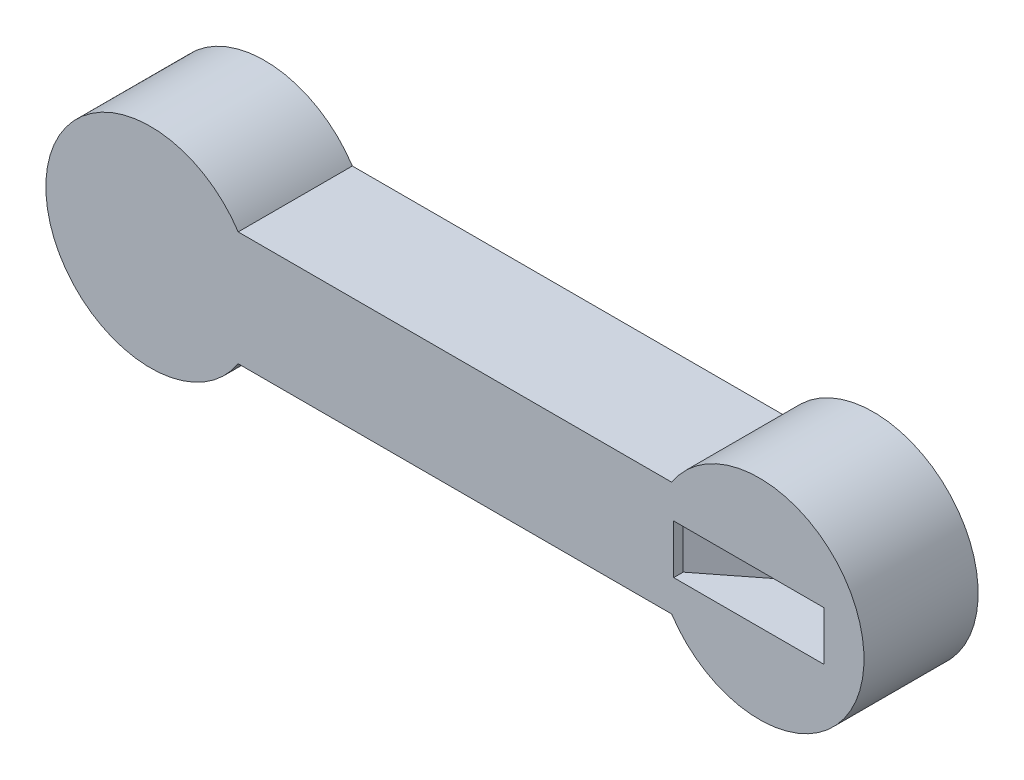
SolidWorks part; units mm, degrees
ref_plane "Front Plane" through (0, 0, 0) normal (0, 0, 1) x (1, 0, 0)
ref_plane "Top Plane" through (0, 0, 0) normal (0, 1, 0) x (1, 0, 0)
ref_plane "Right Plane" through (0, 0, 0) normal (1, 0, 0) x (0, 0, -1)
sketch "Sketch1" plane through (0, 0, 0) normal (0, 0, 1) x (1, 0, 0)
  line L1 (0, 15) -> (160, 15)
  line L2 (0, 15) -> (0, -15)
  line L3 (0, -15) -> (160, -15)
  line L4 (160, 15) -> (160, -15)
  circle A0 centre (0, 0) radius 27.5
  circle A1 centre (160, 0) radius 27.5
  circle A2 centre (0, 0) radius 20
  point P9 (0, 0)
  dimension "D1" = 55
  dimension "D4" = 55
  dimension "D5" = 40
  dimension "D2" = 160
  dimension "D3" = 30
extrude "Boss-Extrude1" add sketch "Sketch1" along normal blind 30 contours L3 A1 L1 L4 | A1 L1 A0 L3 | L1 A1 L3 L4 | A2 L3 A0 L1 | A2 L1 A0 L3 | L3 A2 L1 L2 | L1 A2 L3 L2
sketch "Sketch16" plane through (0, 0, 0) normal (0, 0, -1) x (-1, 0, 0)
  line L0 (-136.9511, -15) -> (-148.5193, -6.45) construction
  line L1 (-148.5193, -6.45) -> (-181.9193, -6.45)
  line L2 (-148.5193, -6.45) -> (-148.5193, 6.45)
  line L3 (-148.5193, 6.45) -> (-181.9193, 6.45)
  line L4 (-181.9193, -6.45) -> (-181.9193, 6.45)
  line L5 (-23.0489, -15) -> (-136.9511, -15) construction
  line L7 (-148.5193, 6.45) -> (-136.9511, 15) construction
  arc A1 (-136.9511, 15) -> (-136.9511, -15) centre (-160, 0) ccw construction
  point P5 (0, 0)
  point P8 (0, 0)
  dimension "D1" = 11.5682
  dimension "D2" = 33.4
  dimension "D3" = 12.9
extrude "Cut-Extrude10" cut sketch "Sketch16" against normal blind 4.5
sketch "Sketch17" plane through (0, 0, 0) normal (0, 0, -1) x (-1, 0, 0)
  line L1 (-176.95, 6.45) -> (-153.4979, 6.45)
  line L2 (-176.95, 6.45) -> (-176.95, -6.45)
  line L3 (-176.95, -6.45) -> (-153.4979, -6.45)
  line L4 (-148.5193, -6.45) -> (-148.5193, 6.45)
  line L5 (-148.5193, 6.45) -> (-181.9193, 6.45)
  line L6 (-181.9193, 6.45) -> (-181.9193, -6.45)
  line L7 (-181.9193, -6.45) -> (-148.5193, -6.45)
  line L8 (-148.5193, -6.45) -> (-148.5193, 6.45)
  line L9 (-148.5193, 6.45) -> (-181.9193, 6.45)
  line L10 (-181.9193, 6.45) -> (-181.9193, -6.45)
  line L11 (-181.9193, -6.45) -> (-148.5193, -6.45)
  line L12 (-153.4979, 6.45) -> (-153.4979, -6.45)
  line M9 (-181.9193, 6.45) -> (-148.5193, 6.45)
  line M11 (-148.5193, -6.45) -> (-181.9193, -6.45)
  dimension "D1" = 0
extrude "Cut-Extrude11" cut sketch "Sketch17" against normal through all contours L12 L2 M9 M11
ref_plane "Plane1" through (0, 0, 0) normal (0, -1, 0) x (-1, 0, 0)
sketch "Sketch18" plane through (0, 0, 0) normal (0, -1, 0) x (-1, 0, 0)
  line L0 (-153.4979, -30) -> (-153.4979, -15)
  line L6 (-137.4979, -30) -> (-137.4979, -27.5)
  line L8 (-181.9193, -4.5) -> (-176.95, -4.5)
  line L9 (-176.95, -4.5) -> (-176.95, -30)
  line L10 (-176.95, -30) -> (-153.4979, -30)
  line L11 (-153.4979, -30) -> (-153.4979, -4.5)
  line L12 (-153.4979, -4.5) -> (-148.5193, -4.5)
  line L13 (-148.5193, -4.5) -> (-148.5193, 0)
  line L14 (-148.5193, 0) -> (-181.9193, 0)
  line L15 (-181.9193, 0) -> (-181.9193, -4.5)
  line L16 (-181.9193, -4.5) -> (-176.95, -4.5)
  line L17 (-176.95, -4.5) -> (-176.95, -30)
  line L18 (-176.95, -30) -> (-153.4979, -30)
  line L19 (-153.4979, -30) -> (-153.4979, -4.5)
  line L20 (-153.4979, -4.5) -> (-148.5193, -4.5)
  line L21 (-148.5193, -4.5) -> (-148.5193, 0)
  line L22 (-148.5193, 0) -> (-181.9193, 0)
  line L23 (-181.9193, 0) -> (-181.9193, -4.5)
  line L26 (-137.4979, -27.5) -> (-153.4979, -15)
  line L28 (-23.0489, -30) -> (-136.9511, -30) construction
  line L30 (-153.4979, -30) -> (-137.4979, -30)
  line L31 (-153.4979, -15) -> (-153.4979, -30)
  point P2 (0, 0)
  dimension "D2" = 15
  dimension "D3" = 16
  dimension "D4" = 2.5
  dimension "D1" = 0
extrude "Cut-Extrude13" cut sketch "Sketch18" against normal mid plane 12.9
sketch "Sketch19" plane through (0, 0, 0) normal (0, 0, -1) x (-1, 0, 0)
  circle A0 centre (0, 0) radius 20
extrude "Cut-Extrude14" cut sketch "Sketch19" against normal mid plane 7.3 contours A0
